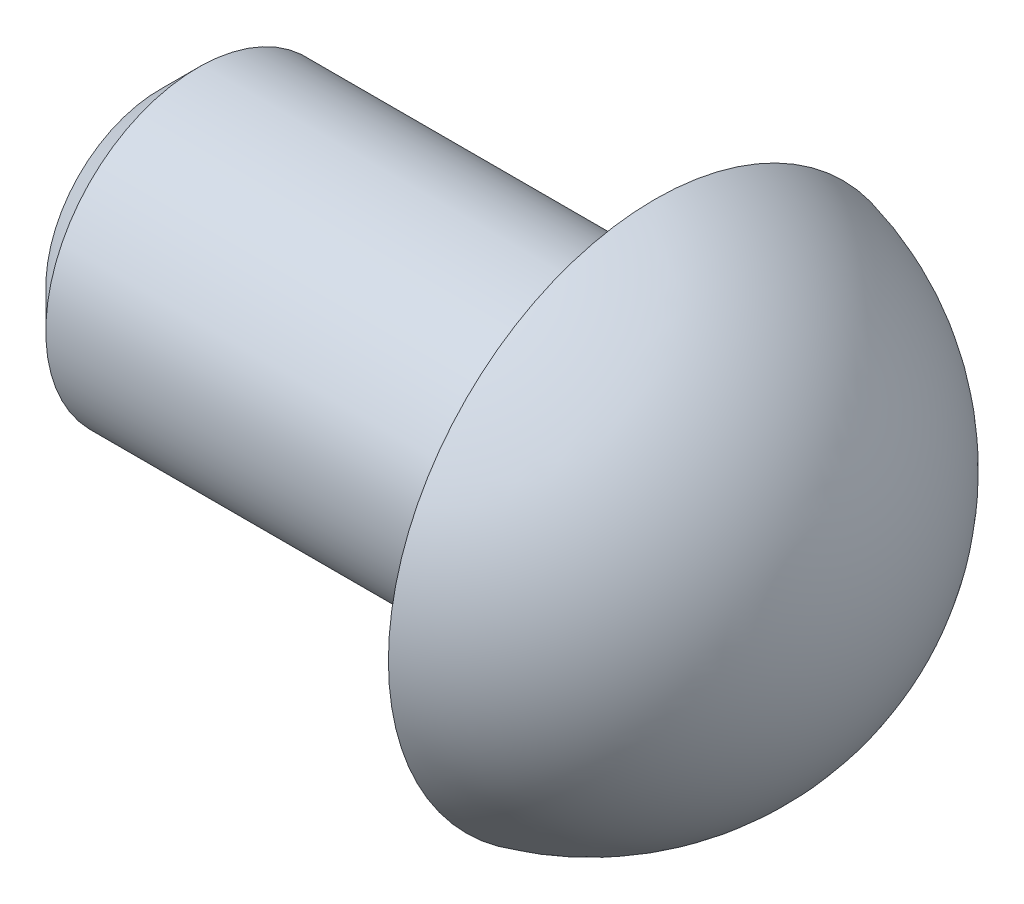
SolidWorks part; units mm, degrees
ref_plane "Front Plane" through (0, 0, 0) normal (0, 0, 1) x (1, 0, 0)
ref_plane "Top Plane" through (0, 0, 0) normal (0, 1, 0) x (1, 0, 0)
ref_plane "Right Plane" through (0, 0, 0) normal (1, 0, 0) x (0, 0, -1)
sketch "Sketch1" plane through (0, 0, 0) normal (1, 0, 0) x (0, 0, -1)
  circle A0 centre (0, 0) radius 2
  dimension "D1" = 4
extrude "Boss-Extrude1" add sketch "Sketch1" against normal blind 6.5
sketch "Sketch3" plane through (0, 0, 0) normal (0, 1, 0) x (1, 0, 0)
  line L0 (-3.0191, 0) -> (2.0861, 0) construction
  line L1 (0, -3.5) -> (0, 0)
  line L2 (0, 0) -> (2.7574, 0)
  arc A0 (0, -3.5) -> (2.7574, 0) centre (-0.8426, 0) ccw
  point P7 (-3.0191, 0)
  dimension "D1" = 3.6
  dimension "D2" = 3.5
revolve "Revolve1" add sketch "Sketch3" angle 360 about L0
chamfer "Chamfer1" distance 0.5 angle 45 1 edges at (-6.5, 0, -2)
